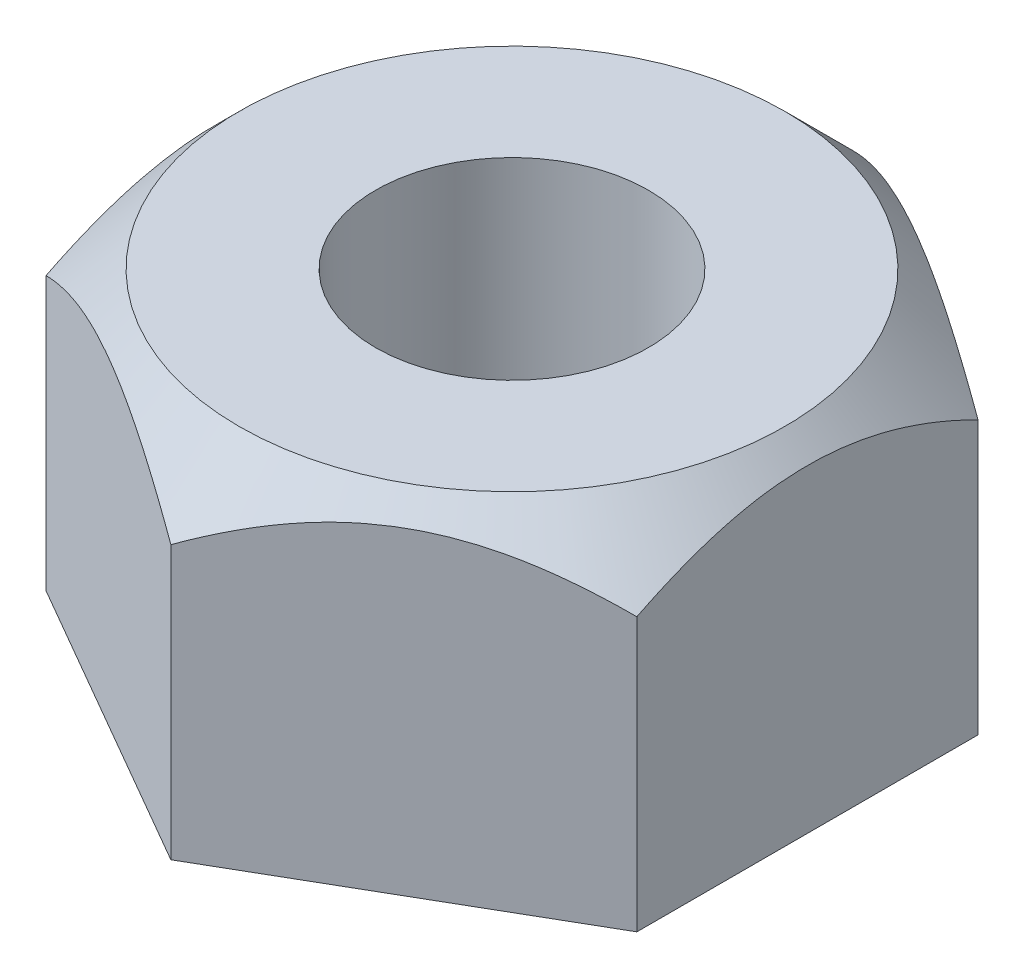
SolidWorks part; units mm, degrees
ref_plane "Front Plane" through (0, 0, 0) normal (0, 0, 1) x (1, 0, 0)
ref_plane "Top Plane" through (0, 0, 0) normal (0, 1, 0) x (1, 0, 0)
ref_plane "Right Plane" through (0, 0, 0) normal (1, 0, 0) x (0, 0, -1)
sketch "Sketch1" plane through (0, 0, 0) normal (0, 1, 0) x (1, 0, 0)
  line L0 (0, 5) -> (0, 0) construction
  line L1 (0, 5) -> (-4.3301, 2.5)
  line L2 (-4.3301, 2.5) -> (-4.3301, -2.5)
  line L3 (-4.3301, -2.5) -> (0, -5)
  line L4 (0, -5) -> (4.3301, -2.5)
  line L5 (4.3301, -2.5) -> (4.3301, 2.5)
  line L6 (4.3301, 2.5) -> (0, 5)
  circle A0 centre (0, 0) radius 4.3301 construction
  circle A1 centre (0, 0) radius 2
  dimension "D2" = 4
  dimension "D1" = 10
extrude "Boss-Extrude1" add sketch "Sketch1" along normal blind 5
sketch "Sketch3" plane through (0, 0, 0) normal (1, 0, 0) x (0, 0, -1)
  line L0 (0, 0) -> (0, 5.6718) construction
  line L1 (-2.5, 0) -> (2.5, 0) construction
  line L2 (4, 5) -> (5, 5)
  line L3 (2.5, 5) -> (5, 5) construction
  line L4 (5, 5) -> (5, 4)
  line L5 (5, 5) -> (5, 0) construction
  line L6 (5, 4) -> (4, 5)
  dimension "D1" = 1
revolve "Cut-Revolve1" cut sketch "Sketch3" angle 360 about L0
